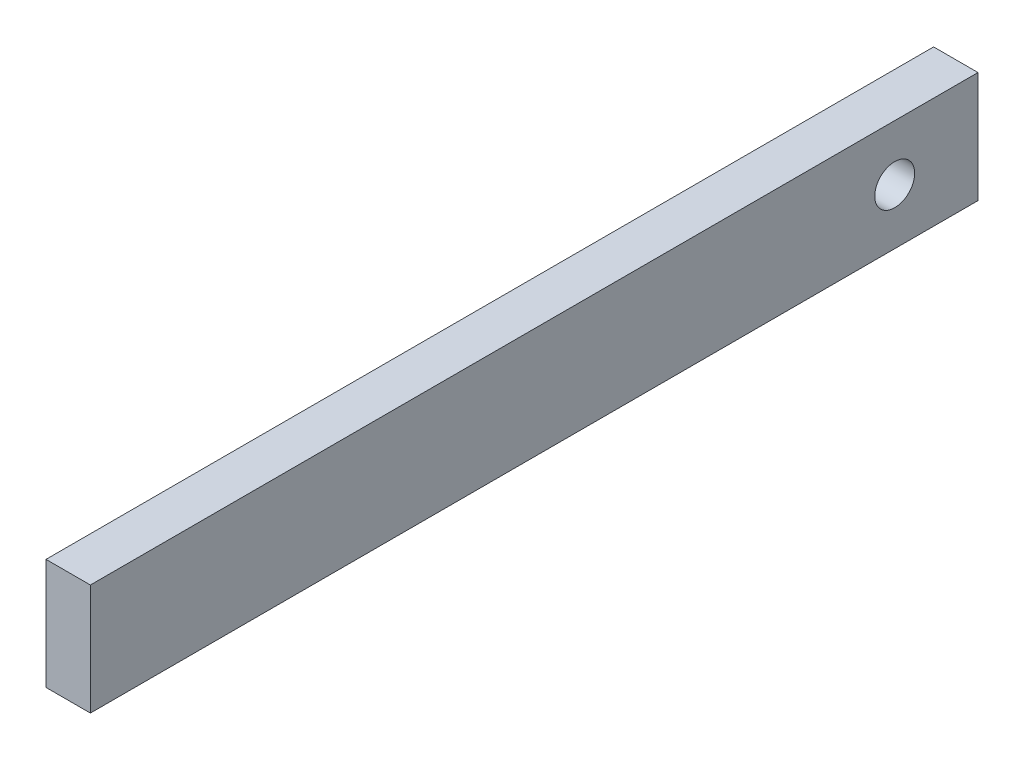
SolidWorks part; units mm, degrees
ref_plane "Front Plane" through (0, 0, 0) normal (0, 0, 1) x (1, 0, 0)
ref_plane "Top Plane" through (0, 0, 0) normal (0, 1, 0) x (1, 0, 0)
ref_plane "Right Plane" through (0, 0, 0) normal (1, 0, 0) x (0, 0, -1)
sketch "Sketch1" plane through (0, 0, 0) normal (1, 0, 0) x (0, 0, -1)
  line L1 (-171.6253, 51.0264) -> (228.3747, 51.0264)
  line L2 (-171.6253, 51.0264) -> (-171.6253, 1.0264)
  line L3 (-171.6253, 1.0264) -> (228.3747, 1.0264)
  line L4 (228.3747, 51.0264) -> (228.3747, 1.0264)
  circle A0 centre (190.838, 26.0264) radius 9
  dimension "D3" = 18
  dimension "D1" = 400
  dimension "D2" = 50
extrude "Boss-Extrude1" add sketch "Sketch1" along normal blind 20
